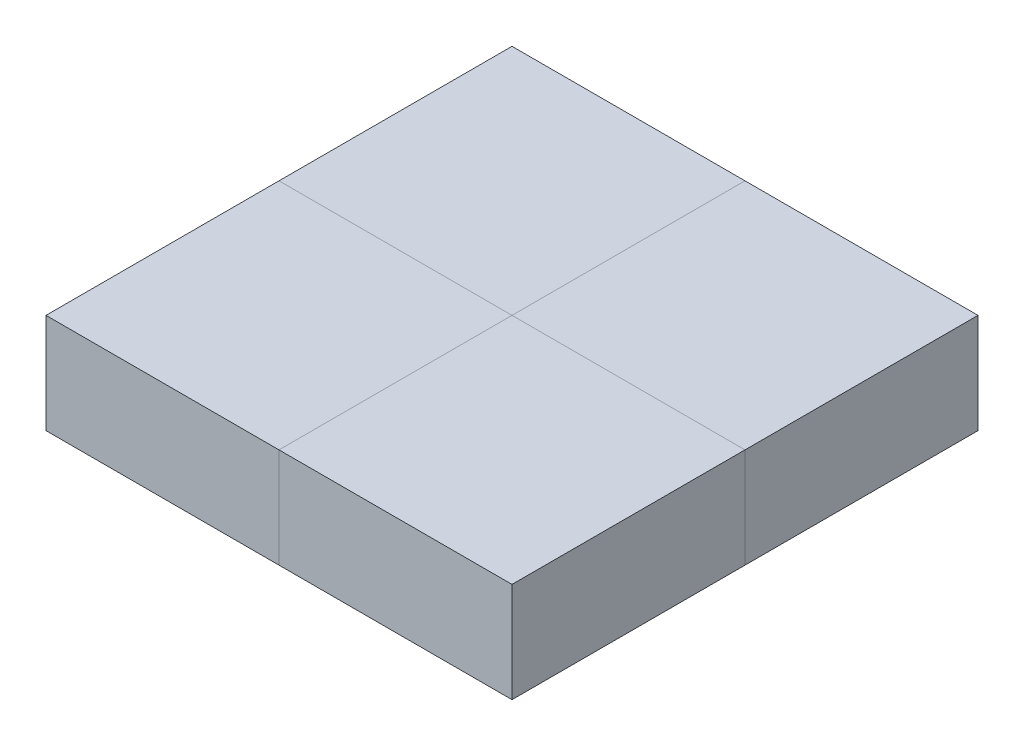
SolidWorks part; units mm, degrees
ref_plane "Front" through (0, 0, 0) normal (0, 0, 1) x (1, 0, 0)
ref_plane "Top" through (0, 0, 0) normal (0, 1, 0) x (1, 0, 0)
ref_plane "Right" through (0, 0, 0) normal (1, 0, 0) x (0, 0, -1)
sketch "Sketch1" plane through (0, 0, 0) normal (0, 1, 0) x (1, 0, 0)
  line L1 (-22.225, 22.225) -> (22.225, 22.225)
  line L2 (-22.225, 22.225) -> (-22.225, -22.225)
  line L3 (-22.225, -22.225) -> (22.225, -22.225)
  line L4 (22.225, 22.225) -> (22.225, -22.225)
  line L5 (-22.225, 22.225) -> (22.225, -22.225) construction
  line L6 (-22.225, -22.225) -> (22.225, 22.225) construction
  circle A0 centre (22.225, -22.225) radius 12.4091 construction
  point P0 (0, 0)
  dimension "D1" = 44.45
extrude "Boss-Extrude1" add sketch "Sketch1" along normal blind 19.05
sketch "Sketch3" plane through (0, 0, 0) normal (0, 1, 0) x (1, 0, 0)
  line L1 (22.225, 22.225) -> (66.675, 22.225)
  line L2 (22.225, 22.225) -> (22.225, -22.225)
  line L3 (22.225, -22.225) -> (66.675, -22.225)
  line L4 (66.675, 22.225) -> (66.675, -22.225)
  dimension "D1" = 44.45
  dimension "D2" = 44.45
extrude "Boss-Extrude2" add sketch "Sketch3" along normal blind 19.05 separate body
sketch "Sketch4" plane through (0, 0, 0) normal (0, 1, 0) x (1, 0, 0)
  line L1 (-22.225, -22.225) -> (22.225, -22.225)
  line L2 (-22.225, -22.225) -> (-22.225, -66.675)
  line L3 (-22.225, -66.675) -> (22.225, -66.675)
  line L4 (22.225, -22.225) -> (22.225, -66.675)
  dimension "D1" = 44.45
extrude "Boss-Extrude3" add sketch "Sketch4" along normal blind 19.05 separate body
sketch "Sketch5" plane through (0, 0, 0) normal (0, 1, 0) x (1, 0, 0)
  line L1 (22.225, -22.225) -> (66.675, -22.225)
  line L2 (22.225, -22.225) -> (22.225, -66.675)
  line L3 (22.225, -66.675) -> (66.675, -66.675)
  line L4 (66.675, -22.225) -> (66.675, -66.675)
  dimension "D1" = 44.45
extrude "Boss-Extrude4" add sketch "Sketch5" along normal blind 19.05 separate body
